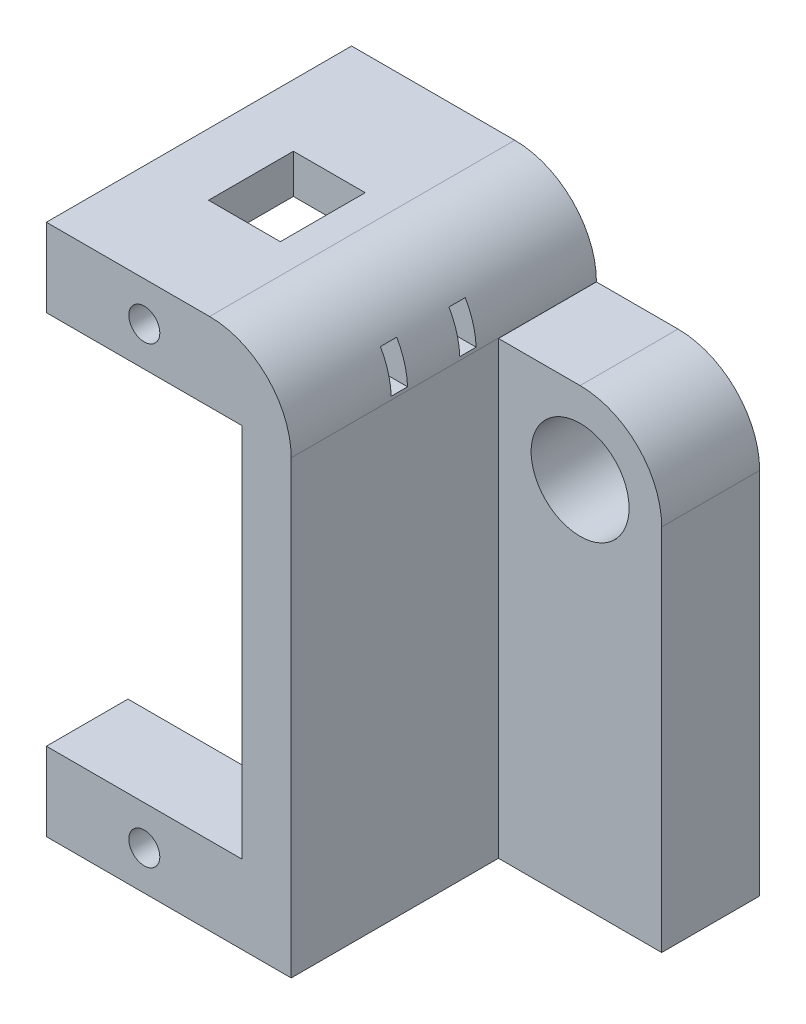
SolidWorks part; units mm, degrees
ref_plane "前视基准面" through (0, 0, 0) normal (0, 0, 1) x (1, 0, 0)
ref_plane "上视基准面" through (0, 0, 0) normal (0, 1, 0) x (1, 0, 0)
ref_plane "右视基准面" through (0, 0, 0) normal (1, 0, 0) x (0, 0, -1)
other "Configuration Table"
sketch "草图1" plane through (0, 0, 0) normal (0, 0, 1) x (1, 0, 0)
  line L0 (6, -2.4) -> (-6, -2.4)
  line L1 (6, -2.4) -> (6, 2.4)
  line L2 (6, 2.4) -> (-6, 2.4)
  line L3 (-6, -2.4) -> (-6, 2.4)
  line L4 (6, -30.2) -> (-6, -30.2)
  line L5 (6, -30.2) -> (6, -25.4)
  line L6 (6, -25.4) -> (-6, -25.4)
  line L7 (-6, -30.2) -> (-6, -25.4)
  line L8 (0, -77.3507) -> (0, -50077.3507) construction
  circle A0 centre (0, 0) radius 0.95
  circle A1 centre (0, -27.8) radius 0.95
  dimension "D10" = 1.9
  dimension "D11" = 1.9
  dimension "D1" = 6
  dimension "D2" = 6
  dimension "D3" = 23
  dimension "D4" = 4.8
  dimension "D5" = 4.8
  dimension "D6" = 2.4
  dimension "D7" = 2.4
  dimension "D8" = 12
  dimension "D9" = 12
extrude "凸台-拉伸1" add sketch "草图1" along normal blind 5
sketch "草图2" plane through (6, 0, 0) normal (1, 0, 0) x (0, 0, -1)
  line L0 (-5, -30.2) -> (0, -30.2) construction
  line L1 (-5, 2.4) -> (10.7, 2.4)
  line L2 (-5, 2.4) -> (-5, -30.2)
  line L3 (-5, -30.2) -> (10.7, -30.2)
  line L4 (10.7, 2.4) -> (10.7, -30.2)
  dimension "D1" = 15.7
extrude "凸台-拉伸2" add sketch "草图2" along normal blind 3
sketch "草图3" plane through (9, 0, 0) normal (1, 0, 0) x (0, 0, -1)
  line L0 (-5, -30.2) -> (10.7, -30.2) construction
  line L1 (10.7, 2.4) -> (7.7, 2.4)
  line L2 (10.7, 2.4) -> (10.7, -30.2)
  line L3 (10.7, -30.2) -> (7.7, -30.2)
  line L4 (7.7, 2.4) -> (7.7, -30.2)
  dimension "D2" = 3
extrude "凸台-拉伸3" add sketch "草图3" along normal blind 10
sketch "草图6" plane through (0, 0, -7.7) normal (0, 0, 1) x (1, 0, 0)
  line L0 (14, 2.4) -> (14, -49997.6) construction
  line L1 (19, 2.4) -> (9, 2.4) construction
  line L2 (11.5541, -7.6) -> (50011.5541, -7.6) construction
  circle A0 centre (14, -7.6169) radius 3
  point P4 (14, 2.4)
  dimension "D2" = 6
  dimension "D1" = 10
extrude "切除-拉伸1" cut sketch "草图6" against normal through all
sketch "草图7" plane through (6, 0, 0) normal (-1, 0, 0) x (0, 0, 1)
  line L0 (-10.7, -30.2) -> (-10.7, 2.4) construction
  line L1 (0, 2.4) -> (-10.7, 2.4)
  line L2 (0, 2.4) -> (0, -2.4)
  line L3 (0, -2.4) -> (-10.7, -2.4)
  line L4 (-10.7, 2.4) -> (-10.7, -2.4)
  line L5 (5, -2.4) -> (0, -2.4) construction
extrude "凸台-拉伸5" add sketch "草图7" along normal blind 12
sketch "草图9" plane through (0, 2.4, 0) normal (0, 1, 0) x (1, 0, 0)
  line L0 (0, 0) -> (0, -50000) construction
  line L1 (-3.5694, 3.7) -> (49996.4306, 3.7) construction
  line L2 (19, 10.7) -> (-6, 10.7) construction
  line L4 (-2.2, 6.3346) -> (2.2, 6.3346)
  line L5 (-2.2, 6.3346) -> (-2.2, 1.1346)
  line L6 (-2.2, 1.1346) -> (2.2, 1.1346)
  line L7 (2.2, 6.3346) -> (2.2, 1.1346)
  line L8 (-2.2, 6.3346) -> (2.2, 1.1346) construction
  line L9 (-2.2, 1.1346) -> (2.2, 6.3346) construction
  point P7 (0, 3.7346)
  dimension "D1" = 7
  dimension "D2" = 5.2
  dimension "D3" = 4.4
extrude "切除-拉伸2" cut sketch "草图9" against normal blind 2.5
sketch "草图10" plane through (0, -0.1, 0) normal (0, 1, 0) x (1, 0, 0)
  line L0 (2.2, 1.1346) -> (2.2, 6.3346) construction
  line L1 (-2.2, 6.3346) -> (2.2, 6.3346)
  line L2 (-2.2, 6.3346) -> (-2.2, 5.3346)
  line L3 (-2.2, 5.3346) -> (2.2, 5.3346)
  line L4 (2.2, 6.3346) -> (2.2, 5.3346)
  line L6 (-2.2, 1.1346) -> (2.2, 1.1346)
  line L7 (-2.2, 1.1346) -> (-2.2, 2.1346)
  line L8 (-2.2, 2.1346) -> (2.2, 2.1346)
  line L9 (2.2, 1.1346) -> (2.2, 2.1346)
  dimension "D1" = 1
  dimension "D2" = 1
extrude "切除-拉伸3" cut sketch "草图10" against normal blind 2.5
sketch "草图11" plane through (2.2, 0, 0) normal (-1, 0, 0) x (0, 0, 1)
  line L5 (-5.3346, -2.4) -> (-6.3346, -2.4) construction
  line L6 (-2.1346, -0.1) -> (-1.1346, -0.1)
  line L7 (-2.1346, -0.1) -> (-2.1346, -2.4)
  line L8 (-2.1346, -2.4) -> (-1.1346, -2.4)
  line L9 (-1.1346, -0.1) -> (-1.1346, -2.4)
  line L10 (-5.3346, -0.1) -> (-6.3346, -0.1)
  line L11 (-5.3346, -0.1) -> (-5.3346, -2.4)
  line L12 (-5.3346, -2.4) -> (-6.3346, -2.4)
  line L13 (-6.3346, -0.1) -> (-6.3346, -2.4)
extrude "切除-拉伸4" cut sketch "草图11" against normal blind 12.5 and the other way blind 12.5
sketch "草图12" plane through (-6, 0, 0) normal (-1, 0, 0) x (0, 0, 1)
  line L1 (-10.7, -2.4) -> (0, -2.4)
  line L2 (-10.7, -2.4) -> (-10.7, 0)
  line L3 (-10.7, 0) -> (0, 0)
  line L4 (0, -2.4) -> (0, 0)
extrude "切除-拉伸5" cut sketch "草图12" against normal blind 12
sketch "草图13" plane through (0, 0, -7.7) normal (0, 0, 1) x (1, 0, 0)
  line L0 (14, -2.6169) -> (9, -2.6169)
  line L1 (9, 2.4) -> (9, -30.2) construction
  line L2 (9, -2.6169) -> (9, 2.4)
  line L3 (9, 2.4) -> (19, 2.4)
  line L4 (19, 2.4) -> (19, -7.6169)
  arc A0 (19, -7.6169) -> (14, -2.6169) centre (14, -7.6169) ccw
extrude "切除-拉伸6" cut sketch "草图13" against normal blind 12
sketch "草图14" plane through (0, 0, -10.7) normal (0, 0, -1) x (-1, 0, 0)
  line L0 (-19, -7.6169) -> (-19, -30.2)
  line L1 (-19, -30.2) -> (-6, -30.2)
  line L2 (-6, -30.2) -> (-6, 0)
  line L3 (-6, 0) -> (6, 0)
  line L4 (6, 0) -> (6, 2.4)
  line L5 (6, 2.4) -> (-9, 2.4)
  line L6 (-9, 2.4) -> (-9, -2.6169)
  line L7 (-9, -2.6169) -> (-14, -2.6169)
  circle A0 centre (-14, -7.6169) radius 3
  arc A1 (-19, -7.6169) -> (-14, -2.6169) centre (-14, -7.6169) cw
  arc A2 (-14, -2.6169) -> (-19, -7.6169) centre (-14, -7.6169) ccw construction
extrude "凸台-拉伸6" add sketch "草图14" along normal blind 3
sketch "草图15" plane through (0, 0, 5) normal (0, 0, 1) x (1, 0, 0)
  line L0 (9, 2.4) -> (-6, 2.4) construction
  line L1 (9, 2.4) -> (9, -30.2) construction
  line L2 (9, -2.6) -> (9, 2.4)
  line L3 (9, 2.4) -> (4, 2.4)
  arc A0 (4, 2.4) -> (9, -2.6) centre (4, -2.6) cw
  dimension "D1" = 5
extrude "切除-拉伸7" cut sketch "草图15" against normal blind 23
